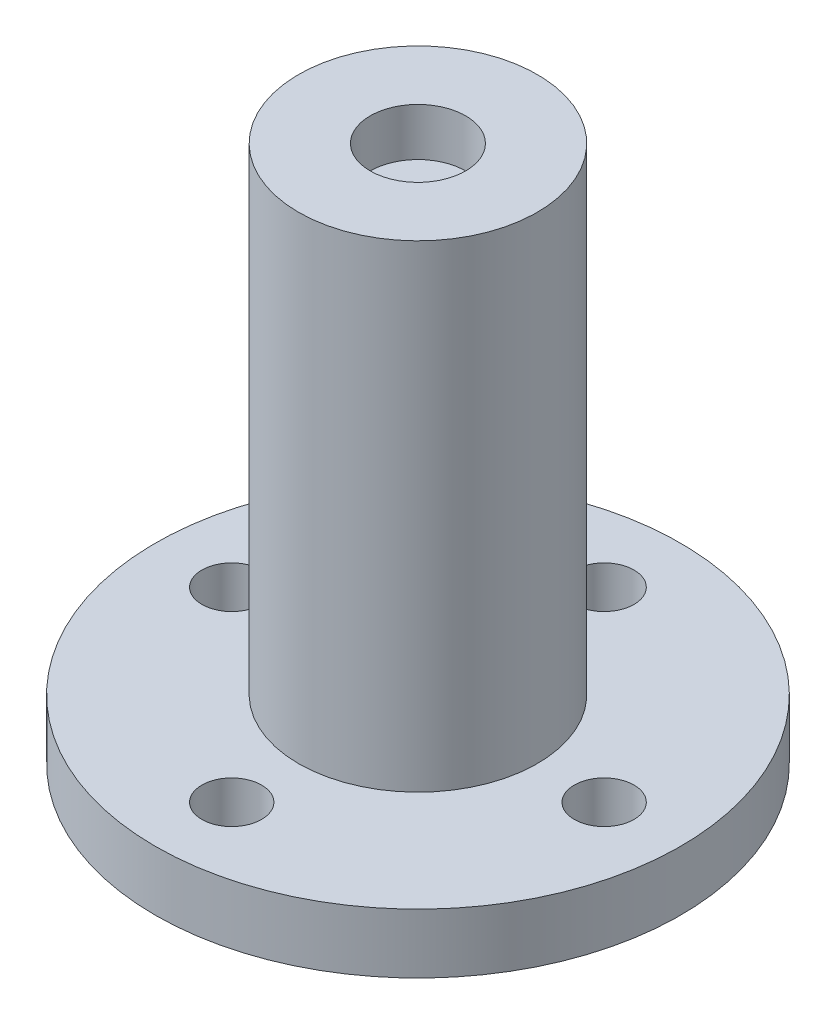
SolidWorks part; units mm, degrees
ref_plane "Front Plane" through (0, 0, 0) normal (0, 0, 1) x (1, 0, 0)
ref_plane "Top Plane" through (0, 0, 0) normal (0, 1, 0) x (1, 0, 0)
ref_plane "Right Plane" through (0, 0, 0) normal (1, 0, 0) x (0, 0, -1)
sketch "Sketch1" plane through (0, 0, 0) normal (0, 1, 0) x (1, 0, 0)
  circle A1 centre (0, 0) radius 7.8 construction
  circle A2 centre (-7.8, 0) radius 1.25
  circle A7 centre (0, 7.8) radius 1.25
  circle A8 centre (7.8, 0) radius 1.25
  circle A9 centre (0, -7.8) radius 1.25
  circle A10 centre (0, 0) radius 11
  point P4 (0, 0)
  point P23 (0, 0)
  dimension "D3" = 15.6
  dimension "D4" = 2.5
  dimension "D6" = 22
  dimension "D8" = 4
extrude "Boss-Extrude2" add sketch "Sketch1" along normal blind 2.5
sketch "Sketch2" plane through (0, 2.5, 0) normal (0, 1, 0) x (1, 0, 0)
  circle A0 centre (0, 0) radius 5.8 construction
  circle A1 centre (0, 0) radius 5
  dimension "D1" = 11.6
  dimension "D2" = 10
extrude "Boss-Extrude3" add sketch "Sketch2" along normal blind 18
sketch "Sketch3" plane through (0, 20.5, 0) normal (0, 1, 0) x (1, 0, 0)
  circle A0 centre (0, 0) radius 2
  circle A1 centre (0, 0) radius 5 construction
  circle A2 centre (0, 0) radius 5
  dimension "D1" = 4
extrude "Boss-Extrude4" add sketch "Sketch3" along normal blind 2
